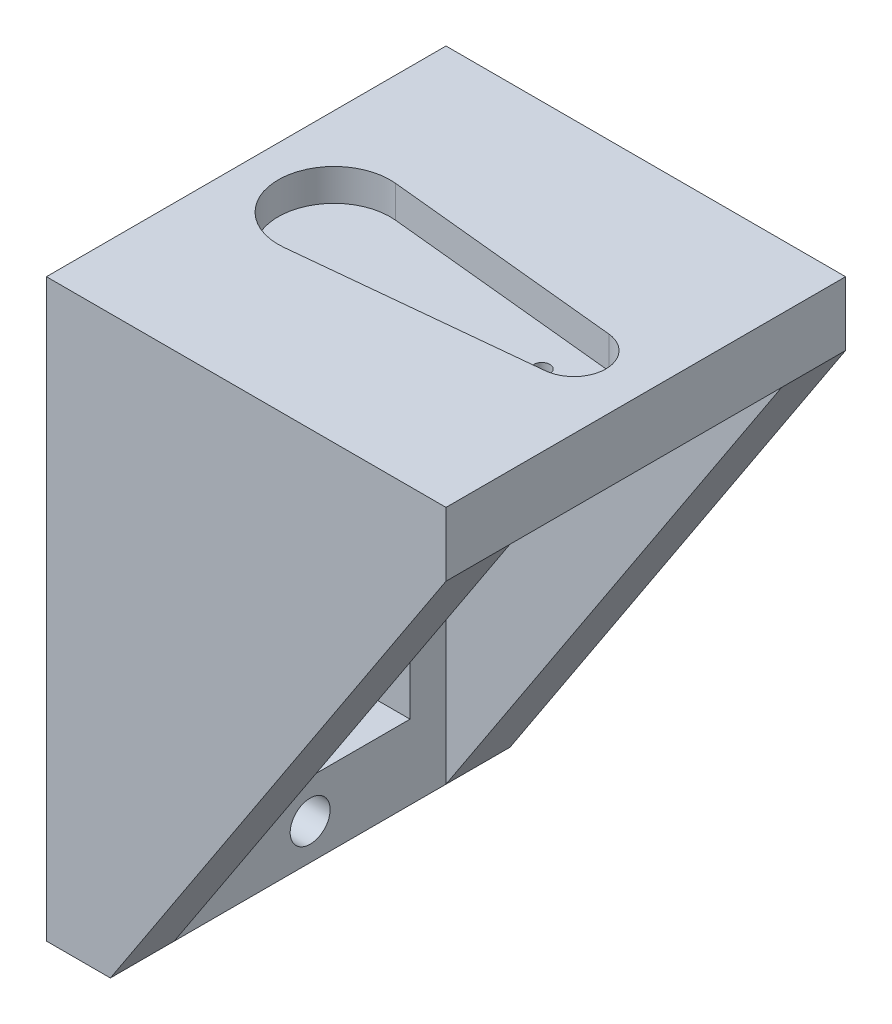
SolidWorks part; units mm, degrees
ref_plane "前视基准面" through (0, 0, 0) normal (0, 0, 1) x (1, 0, 0)
ref_plane "上视基准面" through (0, 0, 0) normal (0, 1, 0) x (1, 0, 0)
ref_plane "右视基准面" through (0, 0, 0) normal (1, 0, 0) x (0, 0, -1)
other "Configuration Table"
sketch "草图2" plane through (0, 0, 0) normal (0, 1, 0) x (1, 0, 0)
  line L1 (-12.5, 12.5) -> (12.5, 12.5)
  line L2 (-12.5, 12.5) -> (-12.5, -12.5)
  line L3 (-12.5, -12.5) -> (12.5, -12.5)
  line L4 (12.5, 12.5) -> (12.5, -12.5)
  line L5 (-12.5, 12.5) -> (12.5, -12.5) construction
  line L6 (-12.5, -12.5) -> (12.5, 12.5) construction
  point P0 (0, 0)
  dimension "D1" = 25
  dimension "D2" = 25
extrude "凸台-拉伸1" add sketch "草图2" along normal blind 4
sketch "草图3" plane through (0, 4, 0) normal (0, 1, 0) x (1, 0, 0)
  line L0 (-6.65, 3.4825) -> (8.2, 1.99)
  line L1 (-6.65, -3.4825) -> (8.2, -1.99)
  line L2 (-6.65, 3.4825) -> (-6.65, -3.4825)
  line L3 (8.2, 1.99) -> (8.2, -1.99)
  line L4 (12.5, -12.5) -> (12.5, 12.5)
  line L5 (12.5, 12.5) -> (-12.5, 12.5)
  line L6 (-12.5, 12.5) -> (-12.5, -12.5)
  line L7 (-12.5, -12.5) -> (12.5, -12.5)
  line L8 (12.5, -12.5) -> (12.5, 12.5)
  line L9 (12.5, 12.5) -> (-12.5, 12.5)
  line L10 (-12.5, 12.5) -> (-12.5, -12.5)
  line L11 (-12.5, -12.5) -> (12.5, -12.5)
  circle A0 centre (8, 0) radius 2
  circle A1 centre (-7, 0) radius 3.5
  point P13 (-12.5, 0)
  dimension "D2" = 7
  dimension "D3" = 4
  dimension "D4" = 15
  dimension "D5" = 5.5
  dimension "D1" = 0
extrude "凸台-拉伸2" add sketch "草图3" along normal blind 4 contours L2 A1 | L2 A1 | A1 L1 A0 L0 | L3 A0 | L3 A0
sketch "草图7" plane through (0, 8, 0) normal (0, 1, 0) x (1, 0, 0)
  line L2 (-6.65, -3.4825) -> (8.2, -1.99)
  line L3 (8.2, 1.99) -> (-6.65, 3.4825)
  line L4 (-6.65, -3.4825) -> (8.2, -1.99)
  line L5 (8.2, 1.99) -> (-6.65, 3.4825)
  arc A2 (-6.65, 3.4825) -> (-6.65, -3.4825) centre (-7, 0) ccw
  arc A3 (8.2, -1.99) -> (8.2, 1.99) centre (8, 0) ccw
  arc A4 (-6.65, 3.4825) -> (-6.65, -3.4825) centre (-7, 0) ccw
  arc A5 (8.2, -1.99) -> (8.2, 1.99) centre (8, 0) ccw
  dimension "D1" = 0
extrude "切除-拉伸1" cut sketch "草图7" against normal blind 6 contours A4 L4 A5 L5
sketch "草图8" plane through (0, 2, 0) normal (0, 1, 0) x (1, 0, 0)
  line L2 (8.2, 1.99) -> (-6.65, 3.4825)
  line L3 (-6.65, -3.4825) -> (8.2, -1.99)
  line L4 (8.2, 1.99) -> (-6.65, 3.4825)
  line L5 (-6.65, -3.4825) -> (8.2, -1.99)
  circle A0 centre (6, 0) radius 0.5
  arc A2 (-6.65, 3.4825) -> (-6.65, -3.4825) centre (-7, 0) ccw
  arc A3 (8.2, -1.99) -> (8.2, 1.99) centre (8, 0) ccw
  arc A4 (-6.65, 3.4825) -> (-6.65, -3.4825) centre (-7, 0) ccw
  arc A5 (8.2, -1.99) -> (8.2, 1.99) centre (8, 0) ccw
  point P8 (0, 0)
  point P9 (0, 0)
  point P10 (0, 0)
  dimension "D2" = 1
  dimension "D3" = 13
  dimension "D1" = 0
extrude "切除-拉伸2" cut sketch "草图8" against normal blind 6 contours A0
sketch "草图11" plane through (0, 0, 0) normal (0, -1, 0) x (1, 0, 0)
  line L0 (-12.5, 12.5) -> (12.5, 12.5) construction
  line L1 (-8.4996, 12.5) -> (-12.5, 12.5)
  line L2 (-8.4996, 12.5) -> (-8.4996, -12.5)
  line L3 (-8.4996, -12.5) -> (-12.5, -12.5)
  line L4 (-12.5, 12.5) -> (-12.5, -12.5)
  line L5 (-8.4996, 12.5) -> (-12.5, -12.5) construction
  line L6 (-8.4996, -12.5) -> (-12.5, 12.5) construction
  line L8 (12.5, 12.5) -> (-8.4996, 12.5)
  line L9 (12.5, 12.5) -> (12.5, 8.5)
  line L10 (12.5, 8.5) -> (-8.4996, 8.5)
  line L11 (-8.4996, 12.5) -> (-8.4996, 8.5)
  line L12 (12.5, 12.5) -> (-8.4996, 8.5) construction
  line L13 (12.5, 8.5) -> (-8.4996, 12.5) construction
  line L14 (12.5, -12.5) -> (-8.4996, -12.5)
  line L15 (12.5, -12.5) -> (12.5, -8.5)
  line L16 (12.5, -8.5) -> (-8.4996, -8.5)
  line L17 (-8.4996, -12.5) -> (-8.4996, -8.5)
  line L18 (12.5, -12.5) -> (-8.4996, -8.5) construction
  line L19 (12.5, -8.5) -> (-8.4996, -12.5) construction
  point P4 (-10.4998, 0)
  point P11 (2.0002, 10.5)
  point P16 (2.0002, -10.5)
  line M11 (12.5, -12.5) -> (12.5, 12.5)
  line M12 (12.5, 12.5) -> (-12.5, 12.5)
  line M13 (-12.5, 12.5) -> (-12.5, -12.5)
  line M14 (-12.5, -12.5) -> (12.5, -12.5)
  dimension "D1" = 4
  dimension "D2" = 4
  dimension "D3" = 4.0004
extrude "凸台-拉伸3" add sketch "草图11" along normal blind 32 contours L10 L2 M11 M12 | L2 M12 M13 M14 | L14 L15 L16 L17
sketch "草图12" plane through (0, 0, -8.5) normal (0, 0, 1) x (1, 0, 0)
  line L0 (12.5, 0) -> (-8.4996, -32)
  line L1 (-8.4996, -32) -> (-8.4996, 0) construction
  line L2 (12.5, -32) -> (-8.4996, -32) construction
  line L3 (-8.4996, -32) -> (12.5, -32)
  line L4 (12.5, -32) -> (12.5, 0)
extrude "切除-拉伸4" cut sketch "草图12" against normal blind 32 and the other way blind 32
sketch "草图13" plane through (-8.4996, 0, 0) normal (1, 0, 0) x (0, 0, -1)
  line L0 (11.3733, -16) -> (-17.6197, -16) construction
  line L1 (0, -34.2811) -> (0, 5.8569) construction
  line L3 (6.25, -4.65) -> (-6.25, -4.65)
  line L4 (6.25, -4.65) -> (6.25, -27.35)
  line L5 (6.25, -27.35) -> (-6.25, -27.35)
  line L6 (-6.25, -4.65) -> (-6.25, -27.35)
  line L7 (6.25, -4.65) -> (-6.25, -27.35) construction
  line L8 (6.25, -27.35) -> (-6.25, -4.65) construction
  circle A0 centre (0, -29.75) radius 1.25
  circle A1 centre (0, -2.25) radius 1.25
  point P5 (0, -16)
  dimension "D3" = 27.5
  dimension "D4" = 2.5
  dimension "D1" = 22.7
  dimension "D2" = 12.5
extrude "切除-拉伸5" cut sketch "草图13" against normal through all
equation "\"27.5、\"=27.9175"
equation "\"2，5\"=3.73119"
